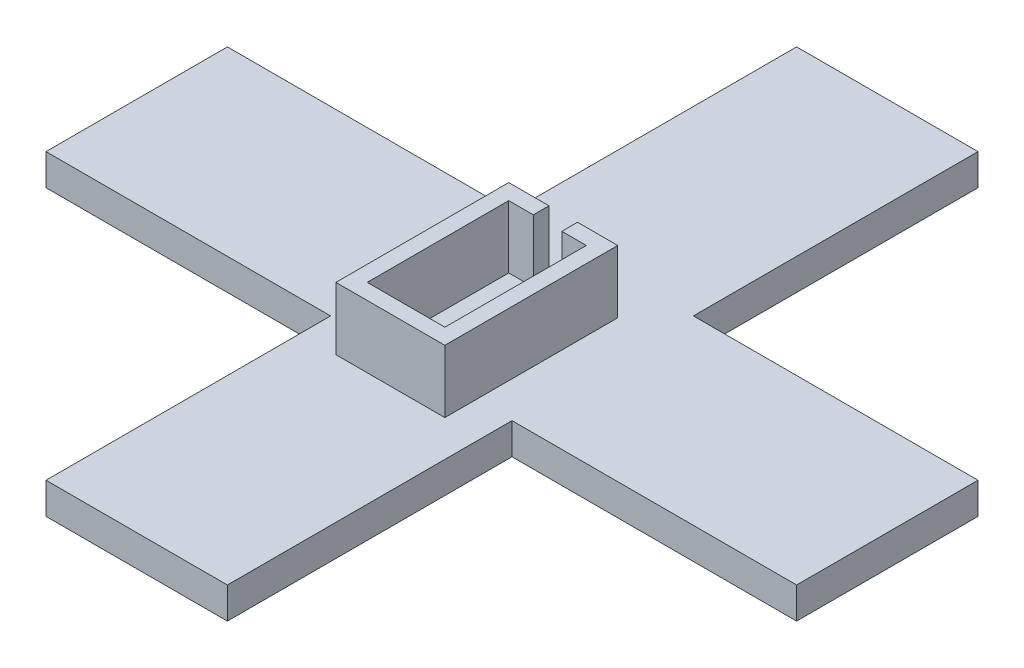
SolidWorks part; units mm, degrees
ref_plane "Front Plane" through (0, 0, 0) normal (0, 0, 1) x (1, 0, 0)
ref_plane "Top Plane" through (0, 0, 0) normal (0, 1, 0) x (1, 0, 0)
ref_plane "Right Plane" through (0, 0, 0) normal (1, 0, 0) x (0, 0, -1)
sketch "Sketch21" plane through (0, 0, 0) normal (0, 1, 0) x (1, 0, 0)
  line L22 (0, 59.92) -> (-14.48, 59.92)
  line L23 (-14.48, 59.92) -> (-14.48, 14.48)
  line L24 (-14.48, 14.48) -> (-59.92, 14.48)
  line L25 (-59.92, -14.48) -> (-14.48, -14.48)
  line L26 (-14.48, -14.48) -> (-14.48, -59.92)
  line L27 (-14.48, -59.92) -> (0, -59.92)
  line L28 (0, -59.92) -> (14.48, -59.92)
  line L29 (14.48, -59.92) -> (14.48, -14.48)
  line L30 (14.48, -14.48) -> (59.92, -14.48)
  line L31 (59.92, 14.48) -> (14.48, 14.48)
  line L32 (14.48, 14.48) -> (14.48, 59.92)
  line L33 (14.48, 59.92) -> (0, 59.92)
  line L34 (-59.92, 0) -> (-59.92, 14.48)
  line L35 (-59.92, -14.48) -> (-59.92, 0)
  line L36 (59.92, 0) -> (59.92, 14.48)
  line L37 (59.92, 0) -> (59.92, -14.48)
  dimension "D1" = 45.44
  dimension "D2" = 14.48
  dimension "D3" = 14.48
  dimension "D4" = 119.84
  dimension "D5" = 119.84
  dimension "D13" = 14.48
extrude "Boss-Extrude18" add sketch "Sketch21" along normal blind 5
sketch "Sketch23" plane through (0, 5, 0) normal (0, 1, 0) x (1, 0, 0)
  line L0 (-8.7, 8.18) -> (-2.28, 8.18)
  line L2 (-8.7, 8.18) -> (-8.7, -19.42)
  line L3 (-8.7, -19.42) -> (8.7, -19.42)
  line L4 (8.7, 8.18) -> (8.7, -19.42)
  line L5 (-2.28, 8.18) -> (-2.28, 5.68)
  line L6 (-2.28, 5.68) -> (-6.2, 5.68)
  line L7 (-6.2, 5.68) -> (-6.2, -16.92)
  line L8 (-6.2, -16.92) -> (6.2, -16.92)
  line L9 (6.2, -16.92) -> (6.2, 5.68)
  line L10 (6.2, 5.68) -> (2.28, 5.68)
  line L11 (2.28, 5.68) -> (2.28, 8.18)
  line L12 (2.28, 8.18) -> (8.7, 8.18)
  line L16 (14.48, 59.92) -> (-14.48, 59.92) construction
  point P0 (0, 0)
  dimension "D1" = 6.2
  dimension "D2" = 12.4
  dimension "D3" = 51.74
  dimension "D4" = 22.6
  dimension "D5" = 2.5
  dimension "D6" = 2.5
  dimension "D7" = 2.5
  dimension "D8" = 2.5
  dimension "D9" = 3.92
  dimension "D10" = 3.92
extrude "Boss-Extrude19" add sketch "Sketch23" along normal blind 10
